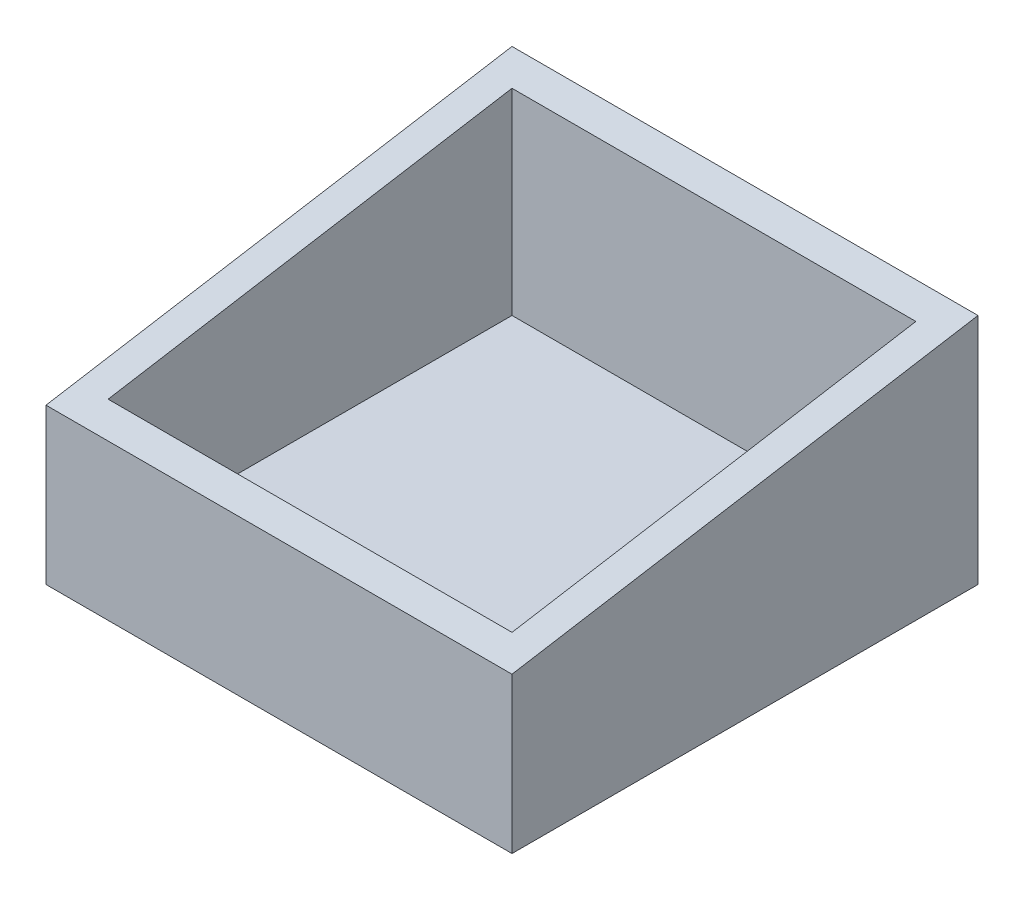
SolidWorks part; units mm, degrees
material "Hêtre"
ref_plane "Plan de face" through (0, 0, 0) normal (0, 0, 1) x (1, 0, 0)
ref_plane "Plan de dessus" through (0, 0, 0) normal (0, 1, 0) x (1, 0, 0)
ref_plane "Plan de droite" through (0, 0, 0) normal (1, 0, 0) x (0, 0, -1)
sketch "Esquisse1" plane through (0, 0, 0) normal (0, 0, 1) x (1, 0, 0)
  line L0 (0, 0) -> (300, 0)
  line L1 (300, 0) -> (300, 150)
  line L2 (300, 150) -> (0, 150)
  line L3 (0, 150) -> (0, 0)
  dimension "D1" = 300
  dimension "D2" = 150
extrude "Boss.-Extru.1" add sketch "Esquisse1" along normal blind 300
sketch "Esquisse5" plane through (300, 0, 0) normal (1, 0, 0) x (0, 0, -1)
  line L0 (0, 150) -> (-300, 100)
  line L1 (-300, 0) -> (-300, 150) construction
  line L2 (-300, 100) -> (-300, 150)
  line L3 (-300, 150) -> (0, 150)
  dimension "D1" = 50
extrude "Enlèv. mat.-Extru.5" cut sketch "Esquisse5" against normal blind 300 contours L0 L2 L3
shell "Coque2" thickness 20
